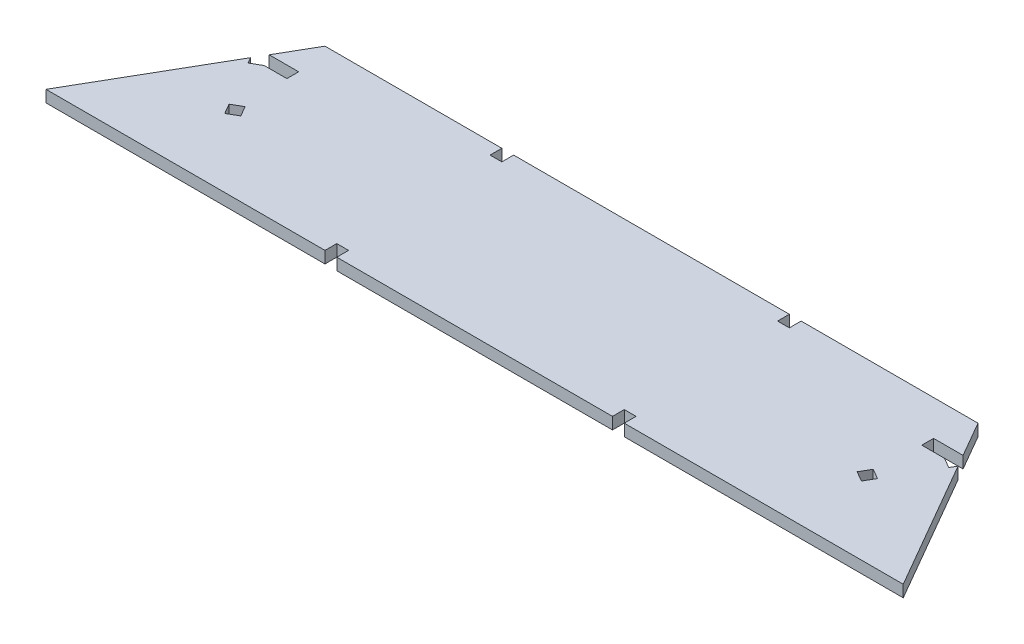
SolidWorks part; units mm, degrees
ref_plane "Front Plane" through (0, 0, 0) normal (0, 0, 1) x (1, 0, 0)
ref_plane "Top Plane" through (0, 0, 0) normal (0, 1, 0) x (1, 0, 0)
ref_plane "Right Plane" through (0, 0, 0) normal (1, 0, 0) x (0, 0, -1)
sketch "Sketch1" plane through (0, 609.6, 0) normal (0, 1, 0) x (1, 0, 0)
  line L12 (923.3117, 0) -> (461.6558, 799.6114)
  line L13 (461.6558, 799.6114) -> (-461.6558, 799.6114)
  line L14 (-461.6558, 799.6114) -> (-923.3117, 0)
  line L15 (-923.3117, 0) -> (-461.6558, -799.6114)
  line L16 (-461.6558, -799.6114) -> (461.6558, -799.6114)
  line L17 (461.6558, -799.6114) -> (923.3117, 0)
  line L18 (923.3117, 0) -> (461.6558, 799.6114)
  line L19 (461.6558, 799.6114) -> (-461.6558, 799.6114)
  line L20 (-461.6558, 799.6114) -> (-923.3117, 0)
  line L21 (-923.3117, 0) -> (-461.6558, -799.6114)
  line L22 (-461.6558, -799.6114) -> (461.6558, -799.6114)
  line L23 (461.6558, -799.6114) -> (923.3117, 0)
  line L24 (-351.6706, 609.1114) -> (-703.3412, 0)
  line L25 (-703.3412, 0) -> (-351.6706, -609.1114)
  line L26 (-351.6706, -609.1114) -> (351.6706, -609.1114)
  line L27 (351.6706, -609.1114) -> (703.3412, 0)
  line L28 (703.3412, 0) -> (351.6706, 609.1114)
  line L29 (351.6706, 609.1114) -> (-351.6706, 609.1114)
  line L30 (-351.6706, 609.1114) -> (-703.3412, 0)
  line L31 (-703.3412, 0) -> (-351.6706, -609.1114)
  line L32 (-351.6706, -609.1114) -> (351.6706, -609.1114)
  line L33 (351.6706, -609.1114) -> (703.3412, 0)
  line L34 (703.3412, 0) -> (351.6706, 609.1114)
  line L35 (351.6706, 609.1114) -> (-351.6706, 609.1114)
  dimension "D1" = 0
  dimension "D2" = 0
extrude "Boss-Extrude1" add sketch "Sketch1" against normal blind 12.7
sketch "Sketch2" plane through (0, 609.6, 0) normal (0, 1, 0) x (1, 0, 0)
  line L0 (-351.6706, -609.1114) -> (-461.6558, -799.6114)
  line L1 (-461.6558, -799.6114) -> (461.6558, -799.6114)
  line L2 (461.6558, -799.6114) -> (351.6706, -609.1114)
  line L3 (351.6706, -609.1114) -> (-351.6706, -609.1114)
extrude "Cut-Extrude1" cut sketch "Sketch2" against normal up to vertex (12.7 mm away) flip side to cut
sketch "Sketch3" plane through (0, 609.6, 0) normal (0, 1, 0) x (1, 0, 0)
  line L3040 (-148.4706, -609.1114) -> (-161.1706, -609.1114)
  line L3041 (-148.4706, -621.8114) -> (-148.4706, -609.1114)
  line L3042 (-161.1706, -621.8114) -> (-148.4706, -621.8114)
  line L3043 (-161.1706, -609.1114) -> (-161.1706, -621.8114)
  line L3044 (-148.4706, -609.1114) -> (-161.1706, -609.1114)
  line L3045 (-148.4706, -621.8114) -> (-148.4706, -609.1114)
  line L3046 (-161.1706, -621.8114) -> (-148.4706, -621.8114)
  line L3047 (-161.1706, -609.1114) -> (-161.1706, -621.8114)
  line L3048 (-342.9, -725.9025) -> (-331.9015, -719.5525)
  line L3049 (-331.9015, -719.5525) -> (-338.2515, -708.554)
  line L3050 (-338.2515, -708.554) -> (-349.25, -714.904)
  line L3051 (-349.25, -714.904) -> (-342.9, -725.9025)
  line L3052 (-342.9, -725.9025) -> (-331.9015, -719.5525)
  line L3053 (-331.9015, -719.5525) -> (-338.2515, -708.554)
  line L3054 (-338.2515, -708.554) -> (-349.25, -714.904)
  line L3055 (-349.25, -714.904) -> (-342.9, -725.9025)
  line L3056 (-148.4706, -786.9114) -> (-161.1706, -786.9114)
  line L3057 (-148.4706, -799.6114) -> (-148.4706, -786.9114)
  line L3058 (-161.1706, -799.6114) -> (-148.4706, -799.6114)
  line L3059 (-161.1706, -786.9114) -> (-161.1706, -799.6114)
  line L3060 (-148.4706, -786.9114) -> (-161.1706, -786.9114)
  line L3061 (-148.4706, -799.6114) -> (-148.4706, -786.9114)
  line L3062 (-161.1706, -799.6114) -> (-148.4706, -799.6114)
  line L3063 (-161.1706, -786.9114) -> (-161.1706, -799.6114)
  line L3064 (-373.6677, -647.2114) -> (-381, -659.9114)
  line L3065 (-381, -659.9114) -> (-377.3338, -666.2614)
  line L3066 (-377.3338, -666.2614) -> (-366.3353, -659.9114)
  line L3067 (-366.3353, -659.9114) -> (-373.6677, -647.2114)
  line L3068 (-373.6677, -647.2114) -> (-381, -659.9114)
  line L3069 (-381, -659.9114) -> (-377.3338, -666.2614)
  line L3070 (-377.3338, -666.2614) -> (-366.3353, -659.9114)
  line L3071 (-366.3353, -659.9114) -> (-373.6677, -647.2114)
  line L3072 (381, -659.9114) -> (373.6677, -647.2114)
  line L3073 (373.6677, -647.2114) -> (366.3353, -659.9114)
  line L3074 (366.3353, -659.9114) -> (377.3338, -666.2614)
  line L3075 (377.3338, -666.2614) -> (381, -659.9114)
  line L3076 (381, -659.9114) -> (373.6677, -647.2114)
  line L3077 (373.6677, -647.2114) -> (366.3353, -659.9114)
  line L3078 (366.3353, -659.9114) -> (377.3338, -666.2614)
  line L3079 (377.3338, -666.2614) -> (381, -659.9114)
  line L3080 (338.2515, -708.554) -> (331.9015, -719.5525)
  line L3081 (349.25, -714.904) -> (338.2515, -708.554)
  line L3082 (342.9, -725.9025) -> (349.25, -714.904)
  line L3083 (331.9015, -719.5525) -> (342.9, -725.9025)
  line L3084 (338.2515, -708.554) -> (331.9015, -719.5525)
  line L3085 (349.25, -714.904) -> (338.2515, -708.554)
  line L3086 (342.9, -725.9025) -> (349.25, -714.904)
  line L3087 (331.9015, -719.5525) -> (342.9, -725.9025)
  line L3088 (148.4706, -621.8114) -> (161.1706, -621.8114)
  line L3089 (148.4706, -609.1114) -> (148.4706, -621.8114)
  line L3090 (161.1706, -609.1114) -> (148.4706, -609.1114)
  line L3091 (161.1706, -621.8114) -> (161.1706, -609.1114)
  line L3092 (148.4706, -621.8114) -> (161.1706, -621.8114)
  line L3093 (148.4706, -609.1114) -> (148.4706, -621.8114)
  line L3094 (161.1706, -609.1114) -> (148.4706, -609.1114)
  line L3095 (161.1706, -621.8114) -> (161.1706, -609.1114)
  line L3096 (161.1706, -786.9114) -> (148.4706, -786.9114)
  line L3097 (161.1706, -799.6114) -> (161.1706, -786.9114)
  line L3098 (148.4706, -799.6114) -> (161.1706, -799.6114)
  line L3099 (148.4706, -786.9114) -> (148.4706, -799.6114)
  line L3100 (161.1706, -786.9114) -> (148.4706, -786.9114)
  line L3101 (161.1706, -799.6114) -> (161.1706, -786.9114)
  line L3102 (148.4706, -799.6114) -> (161.1706, -799.6114)
  line L3103 (148.4706, -786.9114) -> (148.4706, -799.6114)
  dimension "D1" = 0
  dimension "D2" = 0
  dimension "D3" = 0
  dimension "D4" = 0
  dimension "D5" = 0
  dimension "D6" = 0
  dimension "D7" = 0
  dimension "D8" = 0
extrude "Cut-Extrude2" cut sketch "Sketch3" against normal up to vertex (12.7 mm away)
sketch "Sketch4" plane through (0, 609.6, 0) normal (0, 1, 0) x (1, 0, 0)
  line L0 (-373.6677, -647.2114) -> (-341.9177, -647.2114)
  line L1 (-341.9177, -647.2114) -> (-341.9177, -659.9114)
  line L2 (-341.9177, -659.9114) -> (-366.3353, -659.9114)
  line L3 (-366.3353, -659.9114) -> (-373.6677, -647.2114)
  line L4 (0, -609.1114) -> (0, -799.6114) construction
  line L11 (-148.4706, -609.1114) -> (148.4706, -609.1114) construction
  line L12 (-148.4706, -799.6114) -> (148.4706, -799.6114) construction
  line L13 (341.9177, -659.9114) -> (366.3353, -659.9114)
  line L14 (341.9177, -647.2114) -> (341.9177, -659.9114)
  line L15 (373.6677, -647.2114) -> (341.9177, -647.2114)
  line L16 (366.3353, -659.9114) -> (373.6677, -647.2114)
  point P14 (-366.3353, -659.9114)
  point P15 (-373.6677, -647.2114)
  dimension "D1" = 31.75
extrude "Cut-Extrude3" cut sketch "Sketch4" against normal up to vertex (12.7 mm away)
